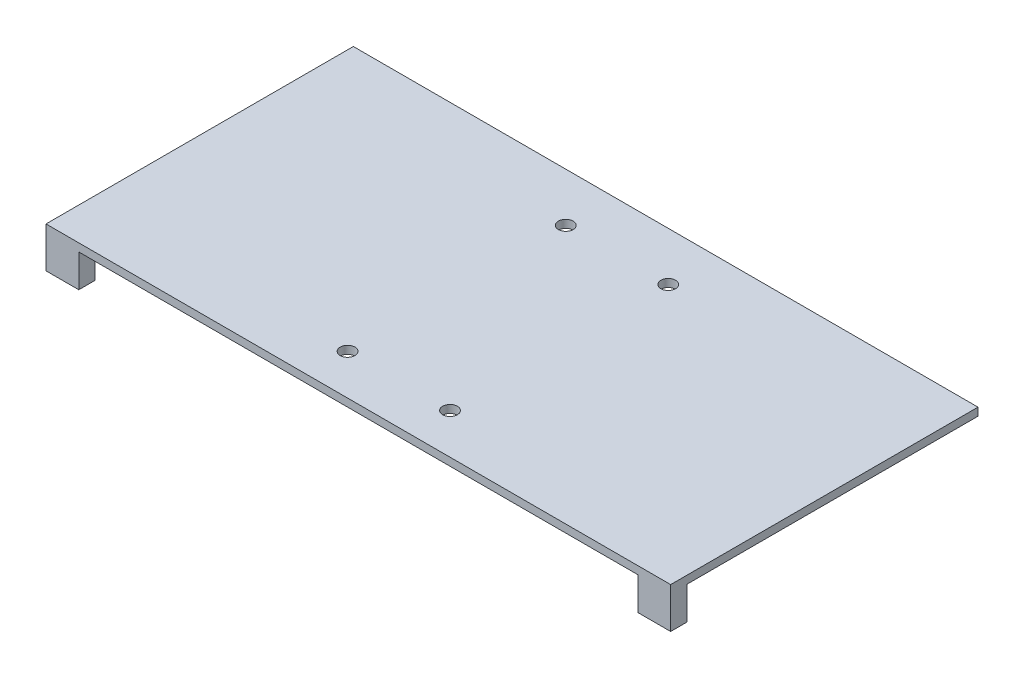
SolidWorks part; units mm, degrees
material "Thornel Mat VMA"
ref_plane "Front Plane" through (0, 0, 0) normal (0, 0, 1) x (1, 0, 0)
ref_plane "Top Plane" through (0, 0, 0) normal (0, 1, 0) x (1, 0, 0)
ref_plane "Right Plane" through (0, 0, 0) normal (1, 0, 0) x (0, 0, -1)
sketch "Sketch1" plane through (0, 0, 0) normal (0, 1, 0) x (1, 0, 0)
  line L1 (0, 0) -> (96.8, 0)
  line L2 (0, 0) -> (0, -47.625)
  line L3 (0, -47.625) -> (96.8, -47.625)
  line L4 (96.8, 0) -> (96.8, -47.625)
  dimension "D1" = 47.625
  dimension "D2" = 96.8
extrude "Boss-Extrude1" add sketch "Sketch1" along normal blind 1.2192
sketch "Sketch5" plane through (0, 1.2192, 0) normal (0, 1, 0) x (1, 0, 0)
  line L0 (96.8, 0) -> (0, 0) construction
  line L1 (56.3375, -7.5406) -> (40.4625, -7.5406) construction
  line L2 (0, 0) -> (0, -47.625) construction
  line L3 (96.8, -23.8125) -> (0, -23.8125) construction
  line L4 (96.8, -47.625) -> (96.8, 0) construction
  circle A0 centre (56.3375, -7.5406) radius 1.143
  circle A1 centre (40.4625, -7.5406) radius 1.143
  dimension "D1" = 2.286
  dimension "D2" = 2.286
  dimension "D3" = 15.875
  dimension "D4" = 7.5406
  dimension "D5" = 40.4625
extrude "Cut-Extrude1" cut sketch "Sketch5" against normal up to next
sketch "Sketch6" plane through (0, 1.2192, 0) normal (0, 1, 0) x (1, 0, 0)
  line L0 (56.3375, -41.3544) -> (40.4625, -41.3544) construction
  line L1 (0, 0) -> (0, -47.625) construction
  line L2 (0, -47.625) -> (96.8, -47.625) construction
  circle A0 centre (56.3375, -41.3544) radius 1.143
  circle A1 centre (40.4625, -41.3544) radius 1.143
  dimension "D1" = 2.286
  dimension "D2" = 2.286
  dimension "D3" = 15.875
  dimension "D4" = 6.2706
  dimension "D5" = 40.4625
extrude "Cut-Extrude2" cut sketch "Sketch6" against normal up to next
sketch "Sketch7" plane through (0, 0, 0) normal (0, -1, 0) x (-1, 0, 0)
  line L0 (-96.8, -47.625) -> (-96.8, -45.085)
  line L1 (-96.8, -47.625) -> (-96.8, 0) construction
  line L2 (-96.8, -45.085) -> (-91.72, -45.085)
  line L3 (-91.72, -45.085) -> (-91.72, -47.625)
  line L4 (0, -47.625) -> (-96.8, -47.625) construction
  line L5 (-91.72, -47.625) -> (-96.8, -47.625)
  line L6 (0, -47.625) -> (-5.08, -47.625)
  line L7 (-5.08, -47.625) -> (-5.08, -45.085)
  line L8 (0, -47.625) -> (0, -45.085)
  line L9 (0, 0) -> (0, -47.625) construction
  line L10 (0, -45.085) -> (-5.08, -45.085)
  point P17 (-3.32, -42.545)
  dimension "D1" = 2.54
  dimension "D2" = 5.08
  dimension "D3" = 2.54
  dimension "D4" = 5.08
extrude "Boss-Extrude2" add sketch "Sketch7" along normal blind 5.08
